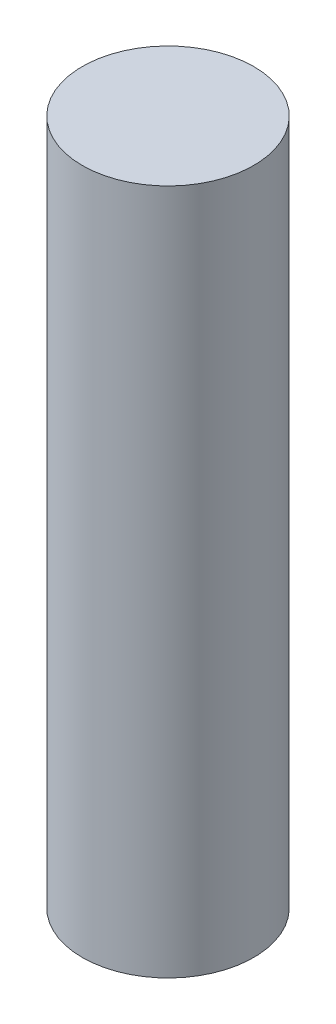
SolidWorks part; units mm, degrees
ref_plane "Front" through (0, 0, 0) normal (0, 0, 1) x (1, 0, 0)
ref_plane "Top" through (0, 0, 0) normal (0, 1, 0) x (1, 0, 0)
ref_plane "Right" through (0, 0, 0) normal (1, 0, 0) x (0, 0, -1)
sketch "Sketch1" plane through (0, 0, 0) normal (0, 1, 0) x (1, 0, 0)
  circle A0 centre (0, 0) radius 9.525
  dimension "D1" = 19.05
extrude "Extrude1" add sketch "Sketch1" along normal blind 76.2
